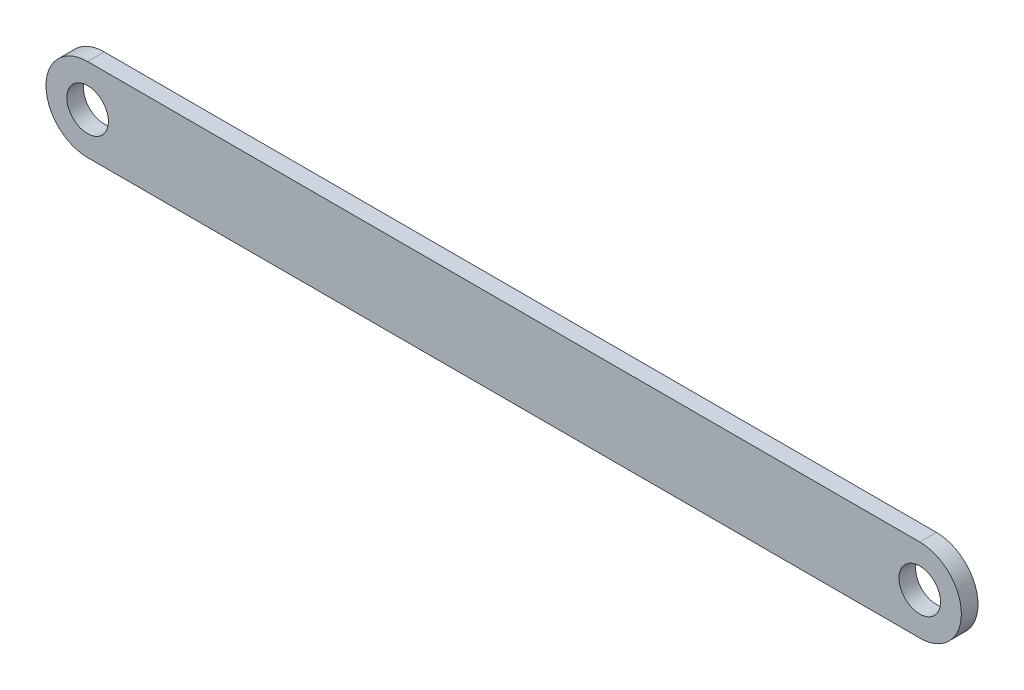
SolidWorks part; units mm, degrees
ref_plane "Front Plane" through (0, 0, 0) normal (0, 0, 1) x (1, 0, 0)
ref_plane "Top Plane" through (0, 0, 0) normal (0, 1, 0) x (1, 0, 0)
ref_plane "Right Plane" through (0, 0, 0) normal (1, 0, 0) x (0, 0, -1)
sketch "Sketch1" plane through (0, 0, 0) normal (0, 0, 1) x (1, 0, 0)
  line L0 (-52.4425, 0) -> (47.5575, 0) construction
  line L1 (-52.4425, 5) -> (47.5575, 5)
  line L2 (-52.4425, -5) -> (47.5575, -5)
  arc A0 (-52.4425, 5) -> (-52.4425, -5) centre (-52.4425, 0) ccw
  arc A1 (47.5575, -5) -> (47.5575, 5) centre (47.5575, 0) ccw
  circle A2 centre (-52.4425, 0) radius 2.5
  circle A3 centre (47.5575, 0) radius 2.5
  point P3 (-2.4425, 0)
  dimension "D1" = 100
  dimension "D2" = 10
extrude "Boss-Extrude1" add sketch "Sketch1" along normal blind 2
